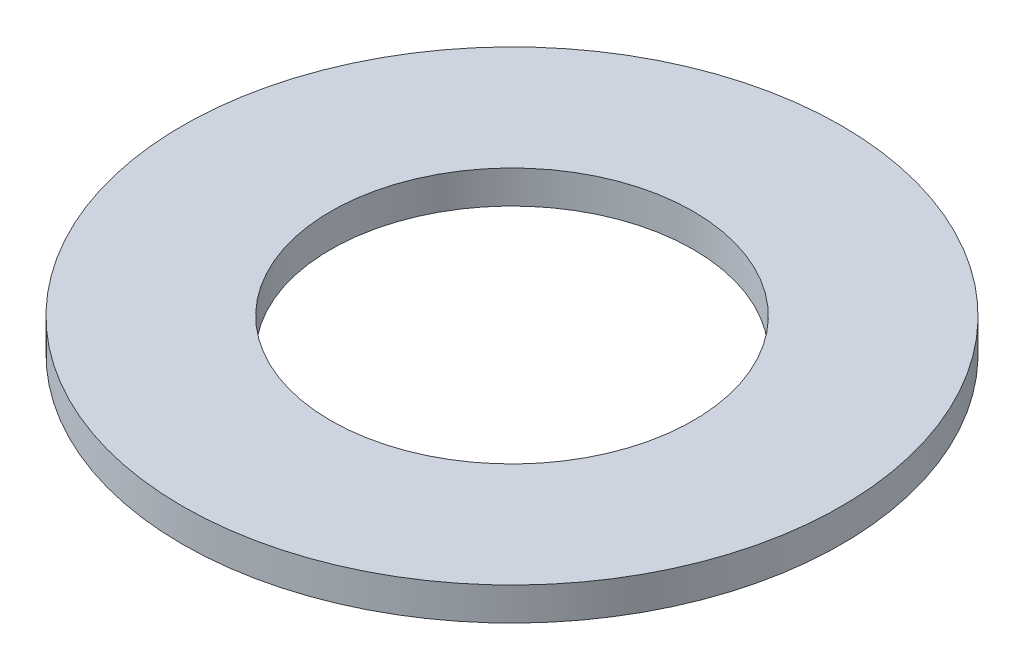
SolidWorks part; units mm, degrees
ref_plane "Ebene vorne" through (0, 0, 0) normal (0, 0, 1) x (1, 0, 0)
ref_plane "Ebene oben" through (0, 0, 0) normal (0, 1, 0) x (1, 0, 0)
ref_plane "Ebene rechts" through (0, 0, 0) normal (1, 0, 0) x (0, 0, -1)
sketch "Skizze1" plane through (0, 0, 0) normal (0, 1, 0) x (1, 0, 0)
  circle A0 centre (0, 0) radius 20
  circle A1 centre (0, 0) radius 11
  dimension "D1" = 22
  dimension "D2" = 40
extrude "Aufsatz-Linear austragen1" add sketch "Skizze1" along normal blind 2
